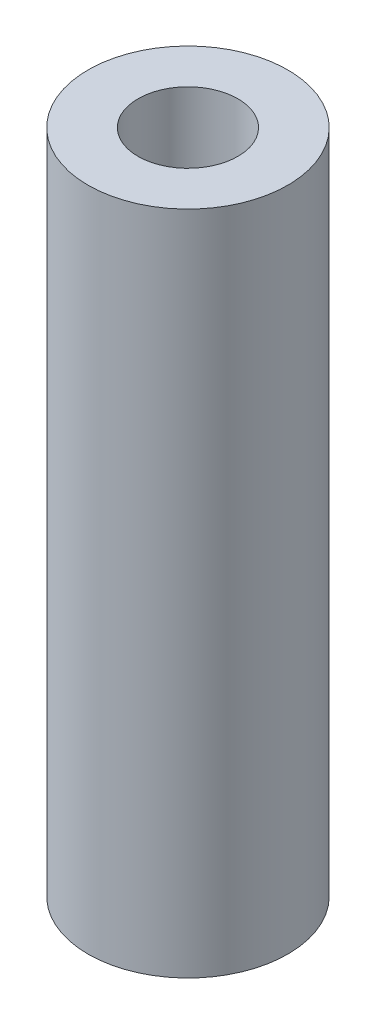
SolidWorks part; units mm, degrees
ref_plane "前视基准面" through (0, 0, 0) normal (0, 0, 1) x (1, 0, 0)
ref_plane "上视基准面" through (0, 0, 0) normal (0, 1, 0) x (1, 0, 0)
ref_plane "右视基准面" through (0, 0, 0) normal (1, 0, 0) x (0, 0, -1)
sketch "草图1" plane through (0, 0, 0) normal (0, 1, 0) x (1, 0, 0)
  circle A0 centre (0, 0) radius 3
  circle A1 centre (0, 0) radius 1.5
  dimension "D1" = 6
  dimension "D2" = 3
extrude "凸台-拉伸1" add sketch "草图1" along normal mid plane 20
